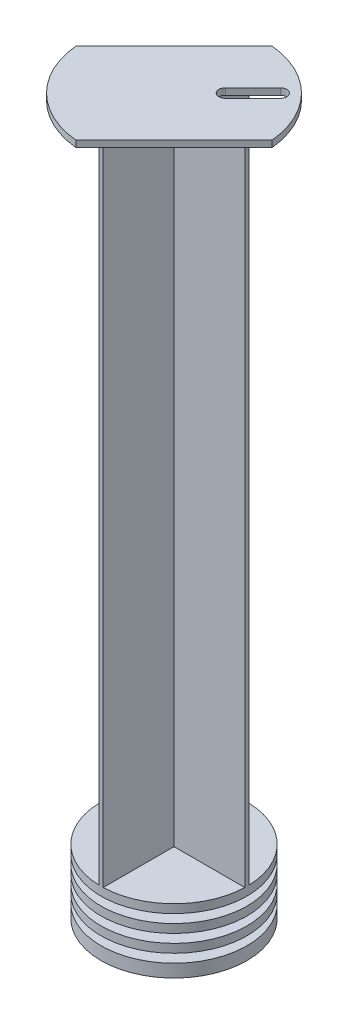
SolidWorks part; units mm, degrees
material "ABS"
ref_plane "前视基准面" through (0, 0, 0) normal (0, 0, 1) x (1, 0, 0)
ref_plane "上视基准面" through (0, 0, 0) normal (0, 1, 0) x (1, 0, 0)
ref_plane "右视基准面" through (0, 0, 0) normal (1, 0, 0) x (0, 0, -1)
sketch "草图1" plane through (0, 0, 0) normal (0, 1, 0) x (1, 0, 0)
  circle A0 centre (0, 0) radius 17
  dimension "D1" = 34
extrude "凸台-拉伸1" add sketch "草图1" along normal blind 15
sketch "草图2" plane through (0, 0, 0) normal (0, 0, 1) x (1, 0, 0)
  line L0 (-17, 15) -> (-17, 0) construction
  line L1 (-17, 13) -> (-11, 13)
  line L2 (-17, 13) -> (-17, 11)
  line L3 (-17, 11) -> (-11, 11)
  line L4 (-11, 13) -> (-11, 11)
  line L5 (17, 15) -> (-17, 15) construction
  line L6 (-17, 9) -> (-11, 9)
  line L7 (-17, 9) -> (-17, 7)
  line L8 (-17, 7) -> (-11, 7)
  line L9 (-11, 9) -> (-11, 7)
  line L10 (-17, 5) -> (-11, 5)
  line L11 (-17, 5) -> (-17, 3)
  line L12 (-17, 3) -> (-11, 3)
  line L13 (-11, 5) -> (-11, 3)
  line L14 (0, 0) -> (0, 25.138) construction
  line L15 (-17, 0) -> (17, 0) construction
  dimension "D1" = 6
  dimension "D2" = 2
  dimension "D3" = 2
  dimension "D5" = 2
  dimension "D4" = 3
revolve "切除-旋转1" cut sketch "草图2" angle 360 about L14
sketch "草图3" plane through (0, 0, 0) normal (0, 0, 1) x (1, 0, 0)
  line L0 (0, 0) -> (-17, 0)
  line L1 (-17, 0) -> (0, -5)
  line L2 (0, -5) -> (0, 0)
  line L3 (0, 0) -> (0, 19.3174) construction
  dimension "D1" = 5
revolve "旋转2" add sketch "草图3" angle 360 about L3
sketch "草图4" plane through (0, 15, 0) normal (0, 1, 0) x (1, 0, 0)
  line L0 (0, 0) -> (36.877, 0) construction
  line L1 (0, 0) -> (0, 37.792) construction
  line L2 (0, 0.5) -> (16.9926, 0.5)
  line L3 (0, -0.5) -> (16.9926, -0.5)
  line L4 (-0.5, 0) -> (-0.5, -16.9926)
  line L5 (0.5, 0) -> (0.5, -16.9926)
  line L6 (0, 0.5) -> (-16.9926, 0.5)
  line L7 (0, -0.5) -> (-16.9926, -0.5)
  line L8 (0.5, 0) -> (0.5, 16.9926)
  line L9 (-0.5, 0) -> (-0.5, 16.9926)
  circle A0 centre (0, 0) radius 0.5
  circle A1 centre (0, 0) radius 17 construction
  arc A2 (16.9926, -0.5) -> (16.9926, 0.5) centre (0, 0) ccw
  arc A3 (-0.5, -16.9926) -> (0.5, -16.9926) centre (0, 0) ccw
  arc A4 (-16.9926, 0.5) -> (-16.9926, -0.5) centre (0, 0) ccw
  arc A5 (0.5, 16.9926) -> (-0.5, 16.9926) centre (0, 0) ccw
  point P26 (0, 0)
  circle M14 centre (0, 0) radius 17
  dimension "D1" = 1
  dimension "D2" = 4
extrude "凸台-拉伸2" add sketch "草图4" along normal blind 150 contours L9 L6 L2 L8 M14 | L4 L9 L6 L7 M14 | L8 L5 L3 L2 M14 | A0 | A0 L6 L9 | L3 L7 L4 L5 M14
sketch "草图5" plane through (0, 165, 0) normal (0, 1, 0) x (1, 0, 0)
  circle A0 centre (0, 0) radius 21
  dimension "D1" = 42
extrude "凸台-拉伸3" add sketch "草图5" along normal blind 1.5
sketch "草图7" plane through (0, 166.5, 0) normal (0, 1, 0) x (1, 0, 0)
  line L0 (0, -21) -> (0, 21) construction
  line L1 (21, 0) -> (-21, 0) construction
  line L2 (0, 0) -> (13.5716, 13.5716) construction
  line L3 (20.9127, 1.9127) -> (-1.9127, -20.9127)
  line L4 (0, 0) -> (19, 0)
  line L5 (12.3744, 12.3744) -> (5.9762, 5.9762) construction
  line L6 (13.435, 11.3137) -> (7.0369, 4.9155)
  line L7 (11.3137, 13.435) -> (4.9155, 7.0369)
  line L8 (1.9127, 20.9127) -> (-20.9127, -1.9127)
  circle A0 centre (0, 0) radius 21 construction
  arc A1 (-1.9127, -20.9127) -> (20.9127, 1.9127) centre (0, 0) ccw
  arc A2 (13.435, 11.3137) -> (11.3137, 13.435) centre (12.3744, 12.3744) ccw
  arc A3 (4.9155, 7.0369) -> (7.0369, 4.9155) centre (5.9762, 5.9762) ccw
  arc A5 (-20.9127, -1.9127) -> (1.9127, 20.9127) centre (0, 0) cw
  point P7 (0, 0)
  point P12 (0, 0)
  point P14 (9.1753, 9.1753)
  point P22 (13.435, 13.435)
  circle M1 centre (0, 0) radius 21
  dimension "D2" = 42
  dimension "D4" = 1.5
  dimension "D1" = 45
  dimension "D3" = 19
  dimension "D5" = 19
extrude "切除-拉伸1" cut sketch "草图7" against normal blind 5 contours L3 M1 | L7 A3 L6 A2 | L8 A5
